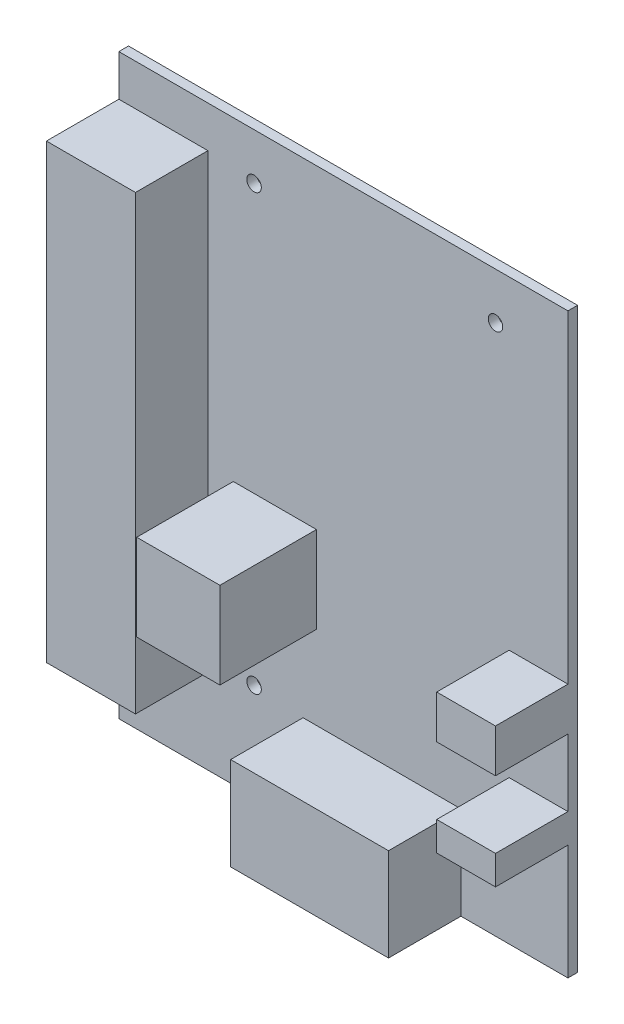
SolidWorks part; units mm, degrees
ref_plane "前视基准面" through (0, 0, 0) normal (0, 0, 1) x (1, 0, 0)
ref_plane "上视基准面" through (0, 0, 0) normal (0, 1, 0) x (1, 0, 0)
ref_plane "右视基准面" through (0, 0, 0) normal (1, 0, 0) x (0, 0, -1)
sketch "草图1" plane through (0, 0, 0) normal (0, 0, 1) x (1, 0, 0)
  line L0 (-38.2114, 42.4797) -> (-66.2114, 42.4797) construction
  line L1 (-38.2114, 42.4797) -> (11.7886, 42.4797) construction
  line L2 (-38.2114, 42.4797) -> (-38.2114, -47.5203) construction
  line L3 (-38.2114, -47.5203) -> (11.7886, -47.5203) construction
  line L4 (11.7886, 42.4797) -> (11.7886, -47.5203) construction
  line L5 (-66.2114, 42.4797) -> (-66.2114, -47.5203)
  line L6 (-66.2114, -47.5203) -> (-38.2114, -47.5203) construction
  line L7 (11.7886, -47.5203) -> (11.7886, -67.5203) construction
  line L8 (11.7886, 42.4797) -> (26.7886, 42.4797) construction
  line L9 (-66.2114, -47.5203) -> (-66.2114, -67.5203)
  line L10 (-66.2114, -67.5203) -> (11.7886, -67.5203)
  line L11 (11.7886, -67.5203) -> (26.7886, -67.5203)
  line L12 (26.7886, -67.5203) -> (26.7886, 42.4797)
  line L13 (26.7886, 42.4797) -> (26.7886, 52.1313)
  line L14 (26.7886, 52.1313) -> (-66.2114, 52.1313)
  line L15 (-66.2114, 52.1313) -> (-66.2114, 42.4797)
  circle A0 centre (-38.2114, 42.4797) radius 1.5
  circle A1 centre (11.7886, 42.4797) radius 1.5
  circle A2 centre (11.7886, -47.5203) radius 1.5
  circle A3 centre (-38.2114, -47.5203) radius 1.5
  dimension "D3" = 20
  dimension "D1" = 50
  dimension "D2" = 90
  dimension "D4" = 15
extrude "凸台-拉伸1" add sketch "草图1" along normal blind 2
sketch "草图2" plane through (0, 0, 2) normal (0, 0, 1) x (1, 0, 0)
  line L0 (-66.2114, 52.1313) -> (-66.2114, -67.5203) construction
  line L1 (-66.2114, 43.5875) -> (-47.7663, 43.5875)
  line L2 (-66.2114, 43.5875) -> (-66.2114, -49.9485)
  line L3 (-66.2114, -49.9485) -> (-47.7663, -49.9485)
  line L4 (-47.7663, 43.5875) -> (-47.7663, -49.9485)
  line L5 (-66.2114, -67.5203) -> (26.7886, -67.5203) construction
  line L6 (-28.0622, -67.5203) -> (4.6327, -67.5203)
  line L7 (-28.0622, -67.5203) -> (-28.0622, -48.2676)
  line L8 (-28.0622, -48.2676) -> (4.6327, -48.2676)
  line L9 (4.6327, -67.5203) -> (4.6327, -48.2676)
  line L10 (26.7886, -67.5203) -> (26.7886, 52.1313) construction
  line L11 (26.7886, -14.819) -> (14.613, -14.819)
  line L12 (26.7886, -14.819) -> (26.7886, -23.759)
  line L13 (26.7886, -23.759) -> (14.613, -23.759)
  line L14 (14.613, -14.819) -> (14.613, -23.759)
  line L16 (26.7886, -37.6724) -> (14.613, -37.6724)
  line L17 (26.7886, -37.6724) -> (26.7886, -43.6898)
  line L18 (26.7886, -43.6898) -> (14.613, -43.6898)
  line L19 (14.613, -37.6724) -> (14.613, -43.6898)
extrude "凸台-拉伸2" add sketch "草图2" along normal blind 15
sketch "草图3" plane through (0, 0, 2) normal (0, 0, 1) x (1, 0, 0)
  line L1 (-42.5094, -13.1227) -> (-25.2849, -13.1227)
  line L2 (-42.5094, -13.1227) -> (-42.5094, -31.0235)
  line L3 (-42.5094, -31.0235) -> (-25.2849, -31.0235)
  line L4 (-25.2849, -13.1227) -> (-25.2849, -31.0235)
extrude "凸台-拉伸3" add sketch "草图3" along normal blind 20
